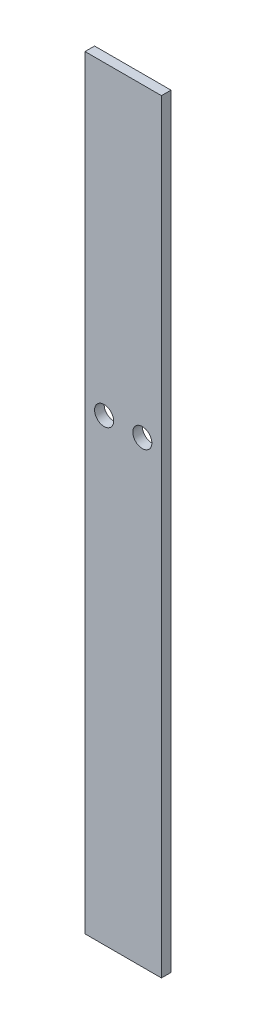
SolidWorks part; units mm, degrees
ref_plane "Front Plane" through (0, 0, 0) normal (0, 0, 1) x (1, 0, 0)
ref_plane "Top Plane" through (0, 0, 0) normal (0, 1, 0) x (1, 0, 0)
ref_plane "Right Plane" through (0, 0, 0) normal (1, 0, 0) x (0, 0, -1)
sketch "Sketch1" plane through (0, 0, 0) normal (0, 0, 1) x (1, 0, 0)
  line L1 (0, 0) -> (38.1, 0)
  line L2 (0, 0) -> (0, 381)
  line L3 (0, 381) -> (38.1, 381)
  line L4 (38.1, 0) -> (38.1, 381)
  circle A0 centre (9.525, 228.6) radius 4.7625
  circle A1 centre (28.575, 228.6) radius 4.7625
  point P9 (28.4638, 251.9448)
  dimension "D3" = 9.525
  dimension "D1" = 381
  dimension "D2" = 38.1
  dimension "D4" = 19.05
  dimension "D5" = 9.525
  dimension "D6" = 152.4
extrude "Boss-Extrude1" add sketch "Sketch1" along normal blind 4.7625
